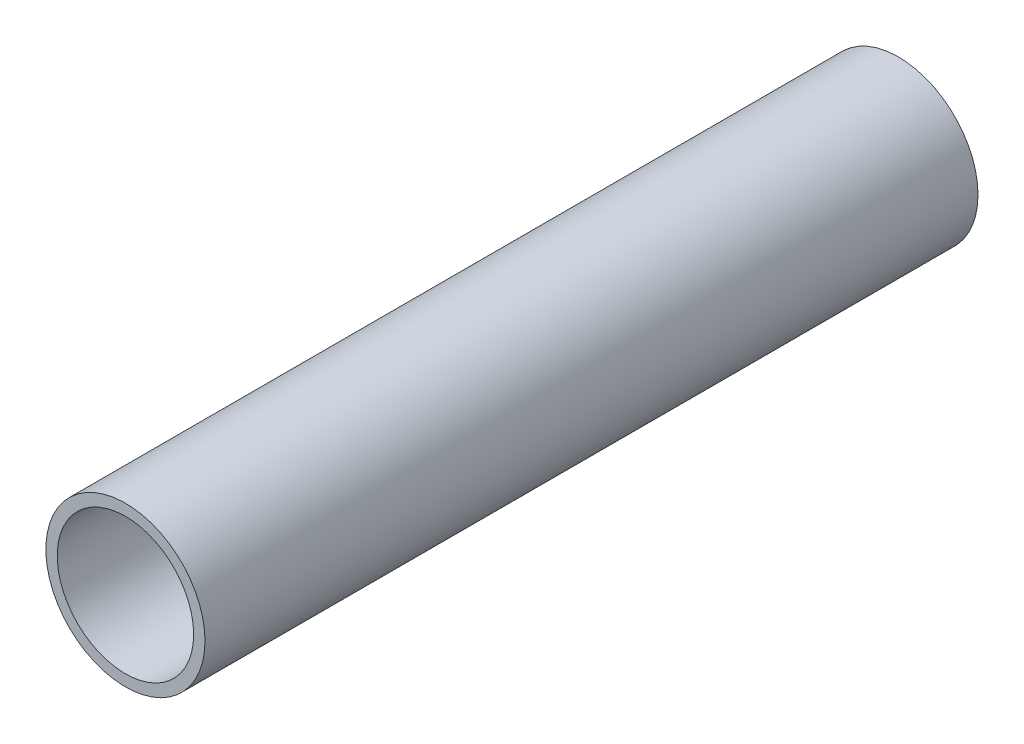
SolidWorks part; units mm, degrees
ref_plane "Face" through (0, 0, 0) normal (0, 0, 1) x (1, 0, 0)
ref_plane "Dessus" through (0, 0, 0) normal (0, 1, 0) x (1, 0, 0)
ref_plane "Droite" through (0, 0, 0) normal (1, 0, 0) x (0, 0, -1)
sketch "Esquisse1" plane through (0, 0, 0) normal (0, 0, 1) x (1, 0, 0)
  circle A0 centre (0, 0) radius 1.75
  circle A1 centre (0, 0) radius 1.5
  dimension "D1" = 3.5
  dimension "D2" = 3
extrude "Base-Extrusion" add sketch "Esquisse1" against normal blind 17
